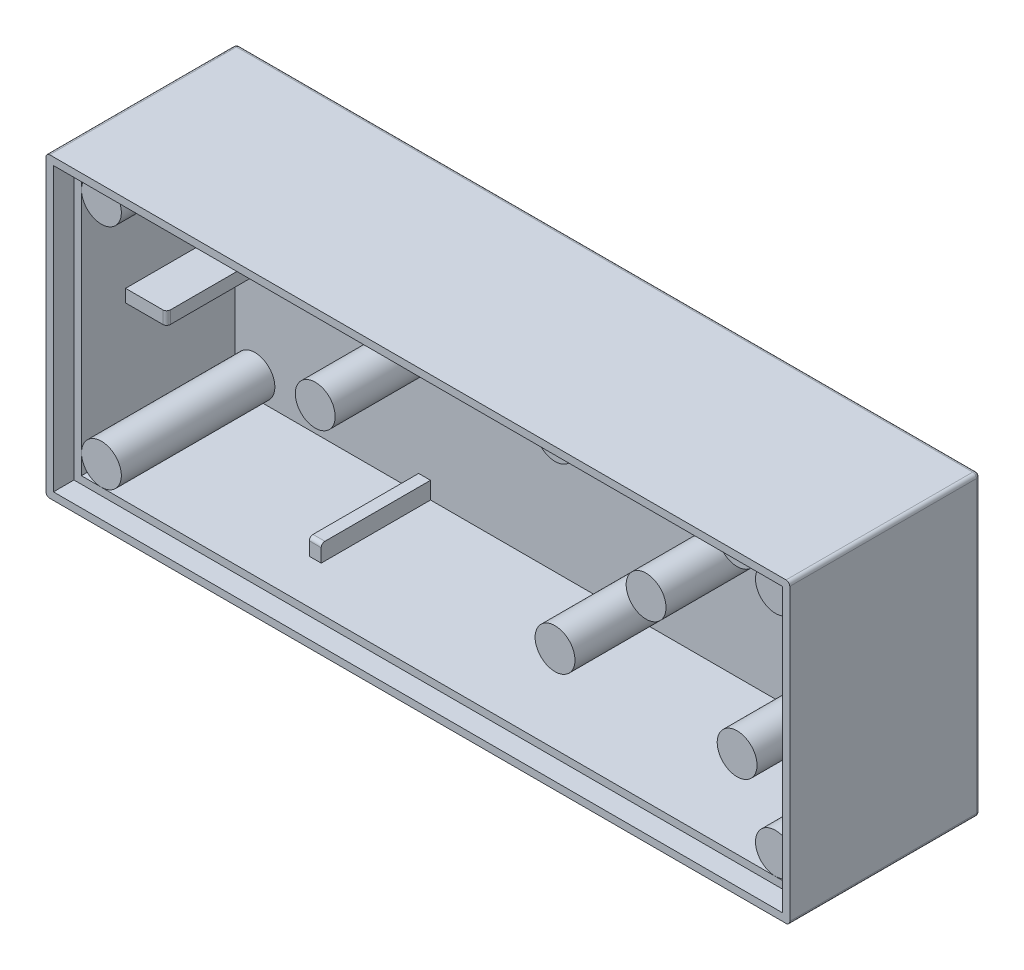
SolidWorks part; units mm, degrees
ref_plane "Ön Düzlem" through (0, 0, 0) normal (0, 0, 1) x (1, 0, 0)
ref_plane "Üst Düzlem" through (0, 0, 0) normal (0, 1, 0) x (1, 0, 0)
ref_plane "Sağ Düzlem" through (0, 0, 0) normal (1, 0, 0) x (0, 0, -1)
sketch "Çizim1" plane through (0, 0, 0) normal (0, 0, 1) x (1, 0, 0)
  line L1 (-42.1848, 19.8128) -> (57.8152, 19.8128)
  line L2 (-42.1848, 19.8128) -> (-42.1848, -20.1872)
  line L3 (-42.1848, -20.1872) -> (57.8152, -20.1872)
  line L4 (57.8152, 19.8128) -> (57.8152, -20.1872)
  dimension "D1" = 100
  dimension "D2" = 40
extrude "Yükseklik-Ekstrüzyon1" add sketch "Çizim1" along normal blind 25.6
sketch "Çizim2" plane through (0, 0, 25.6) normal (0, 0, 1) x (1, 0, 0)
  line L0 (57.8152, 19.8128) -> (-42.1848, 19.8128) construction
  line L1 (-40.1848, 17.8128) -> (55.8152, 17.8128)
  line L2 (-40.1848, 17.8128) -> (-40.1848, -18.1872)
  line L3 (-40.1848, -18.1872) -> (55.8152, -18.1872)
  line L4 (55.8152, 17.8128) -> (55.8152, -18.1872)
  line L5 (-42.1848, 19.8128) -> (-42.1848, -20.1872) construction
  line L6 (-42.1848, -20.1872) -> (57.8152, -20.1872) construction
  line L7 (57.8152, -20.1872) -> (57.8152, 19.8128) construction
  dimension "D1" = 2
  dimension "D2" = 2
  dimension "D3" = 2
  dimension "D4" = 2
extrude "Kes-Ekstrüzyon1" cut sketch "Çizim2" against normal blind 23.4
sketch "Çizim5" plane through (0, 0, 2.2) normal (0, 0, 1) x (1, 0, 0)
  line L0 (-40.1848, 17.8128) -> (-40.1848, -18.1872) construction
  line L1 (55.8152, 17.8128) -> (-40.1848, 17.8128) construction
  line L2 (-40.1848, -18.1872) -> (55.8152, -18.1872) construction
  line L3 (-40.1848, -18.1872) -> (55.8152, -18.1872) construction
  line L4 (55.8152, -18.1872) -> (55.8152, 17.8128) construction
  line L5 (55.8152, -18.1872) -> (55.8152, 17.8128) construction
  circle A0 centre (-37.4948, 15.1228) radius 2.68
  circle A1 centre (-37.4948, -15.4972) radius 2.68
  circle A2 centre (53.1252, -15.4972) radius 2.68
  circle A3 centre (53.1252, 15.1228) radius 2.68
  dimension "D1" = 5.36
  dimension "D2" = 5.36
  dimension "D3" = 5.36
  dimension "D4" = 5.36
  dimension "D5" = 2.69
  dimension "D6" = 2.69
  dimension "D7" = 2.69
  dimension "D8" = 2.69
  dimension "D9" = 2.69
  dimension "D10" = 2.69
  dimension "D11" = 2.69
  dimension "D12" = 2.69
extrude "Yükseklik-Ekstrüzyon6" add sketch "Çizim5" along normal blind 22.42
sketch "Çizim6" plane through (0, 0, 25.6) normal (0, 0, 1) x (1, 0, 0)
  line L0 (57.8152, 19.8128) -> (-42.1848, 19.8128) construction
  line L1 (-41.1848, 18.8128) -> (56.8152, 18.8128)
  line L2 (-41.1848, 18.8128) -> (-41.1848, -19.1872)
  line L3 (-41.1848, -19.1872) -> (56.8152, -19.1872)
  line L4 (56.8152, 18.8128) -> (56.8152, -19.1872)
  line L5 (-42.1848, 19.8128) -> (-42.1848, -20.1872) construction
  line L6 (-42.1848, -20.1872) -> (57.8152, -20.1872) construction
  line L7 (57.8152, -20.1872) -> (57.8152, 19.8128) construction
  dimension "D1" = 1
  dimension "D2" = 1
  dimension "D3" = 1
  dimension "D4" = 1
extrude "Kes-Ekstrüzyon2" cut sketch "Çizim6" against normal blind 2.76
sketch "Çizim7" plane through (0, 0, 2.2) normal (0, 0, 1) x (1, 0, 0)
  line L0 (55.8152, -18.1872) -> (55.8152, 17.8128) construction
  line L1 (55.8152, 0.6628) -> (50.2952, 0.6628)
  line L2 (55.8152, 0.6628) -> (55.8152, -1.0372)
  line L3 (55.8152, -1.0372) -> (50.2952, -1.0372)
  line L4 (50.2952, 0.6628) -> (50.2952, -1.0372)
  line L5 (57.8152, 19.8128) -> (-42.1848, 19.8128) construction
  line L7 (-40.1848, -18.1872) -> (-40.1848, 17.8128) construction
  line L8 (-40.1848, 0.6628) -> (-34.6648, 0.6628)
  line L9 (-40.1848, 0.6628) -> (-40.1848, -1.0372)
  line L10 (-40.1848, -1.0372) -> (-34.6648, -1.0372)
  line L11 (-34.6648, 0.6628) -> (-34.6648, -1.0372)
  line L12 (-42.1848, -20.1872) -> (57.8152, -20.1872) construction
  point P6 (55.8152, -0.1872)
  point P9 (-40.1848, -0.1872)
  dimension "D1" = 1.7
  dimension "D2" = 5.52
  dimension "D3" = 20
  dimension "D4" = 5.52
  dimension "D5" = 1.7
  dimension "D6" = 20
extrude "Yükseklik-Ekstrüzyon7" add sketch "Çizim7" along normal blind 14.7
sketch "Çizim8" plane through (0, 0, 2.2) normal (0, 0, 1) x (1, 0, 0)
  line L0 (55.8152, 17.8128) -> (-40.1848, 17.8128) construction
  line L1 (-15.4848, 17.8128) -> (-13.8848, 17.8128)
  line L2 (-15.4848, 17.8128) -> (-15.4848, 15.5128)
  line L3 (-15.4848, 15.5128) -> (-13.8848, 15.5128)
  line L4 (-13.8848, 17.8128) -> (-13.8848, 15.5128)
  line L5 (-42.1848, 19.8128) -> (-42.1848, -20.1872) construction
  line L6 (-40.1848, -18.1872) -> (55.8152, -18.1872) construction
  line L7 (-15.4848, -18.1872) -> (-13.8848, -18.1872)
  line L8 (-15.4848, -18.1872) -> (-15.4848, -15.8872)
  line L9 (-15.4848, -15.8872) -> (-13.8848, -15.8872)
  line L10 (-13.8848, -18.1872) -> (-13.8848, -15.8872)
  dimension "D1" = 1.6
  dimension "D2" = 2.3
  dimension "D3" = 28.3
  dimension "D4" = 1.6
  dimension "D5" = 2.3
  dimension "D6" = 28.3
extrude "Yükseklik-Ekstrüzyon8" add sketch "Çizim8" along normal blind 14.7
sketch "Çizim9" plane through (0, 0, 2.2) normal (0, 0, 1) x (1, 0, 0)
  line L0 (57.8152, 19.8128) -> (-42.1848, 19.8128) construction
  line L2 (57.8152, -20.1872) -> (57.8152, 19.8128) construction
  circle A1 centre (42.0352, 12.0528) radius 2.68
  circle A2 centre (42.0352, -12.4272) radius 2.68
  circle A3 centre (17.5552, 12.0528) radius 2.68
  circle A4 centre (17.5552, -12.4272) radius 2.68
  circle A5 centre (29.7952, -0.1872) radius 2.68
  circle A6 centre (-14.6848, -0.1872) radius 2.68
  dimension "D1" = 5.36
  dimension "D4" = 5.36
  dimension "D7" = 5.36
  dimension "D8" = 5.36
  dimension "D2" = 7.76
  dimension "D3" = 15.78
  dimension "D5" = 24.48
  dimension "D6" = 12.24
extrude "Yükseklik-Ekstrüzyon9" add sketch "Çizim9" along normal blind 14.7
fillet "Radyus1" radius 0.5 12 edges at (50.2952, -0.1872, 16.9) (-14.6848, 15.5128, 16.9) (-34.6648, -0.1872, 16.9) (-14.6848, -15.8872, 16.9) (-42.1848, 19.8128, 12.8) (7.8152, 19.8128, 0) (57.8152, 19.8128, 12.8) (57.8152, -20.1872, 12.8) (57.8152, -0.1872, 0) (-42.1848, -20.1872, 12.8) (7.8152, -20.1872, 0) (-42.1848, -0.1872, 0)
